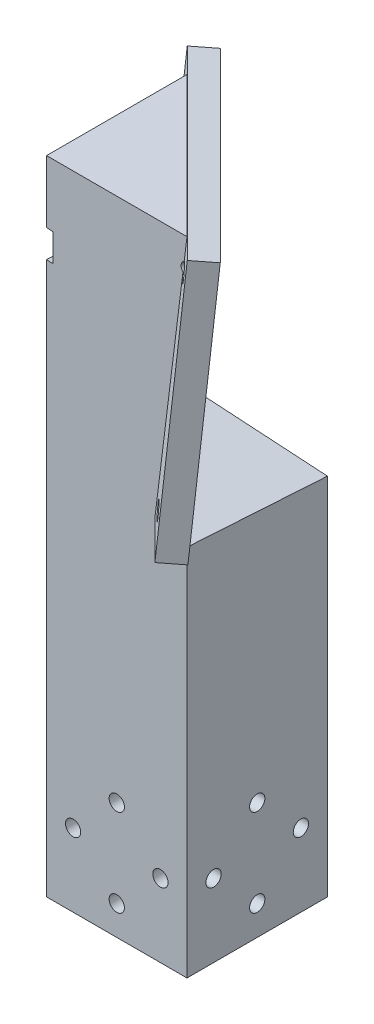
SolidWorks part; units mm, degrees
ref_plane "Front Plane" through (0, 0, 0) normal (0, 0, 1) x (1, 0, 0)
ref_plane "Top Plane" through (0, 0, 0) normal (0, 1, 0) x (1, 0, 0)
ref_plane "Right Plane" through (0, 0, 0) normal (1, 0, 0) x (0, 0, -1)
sketch "Sketch1" plane through (0, 0, 0) normal (0, 1, 0) x (1, 0, 0)
  line L1 (-15.2813, -15.2813) -> (15.2813, -15.2813)
  line L2 (-15.2813, -15.2813) -> (-15.2813, 15.2813)
  line L3 (-15.2813, 15.2813) -> (15.2813, 15.2813)
  line L4 (15.2813, -15.2813) -> (15.2813, 15.2813)
  line L5 (-15.2813, -15.2813) -> (15.2813, 15.2813) construction
  line L6 (-15.2813, 15.2813) -> (15.2813, -15.2813) construction
  point P0 (0, 0)
  point P5 (0, 0)
  dimension "D1" = 30.5626
extrude "Boss-Extrude1" add sketch "Sketch1" along normal blind 139.7 contours L1 L4 L3 L2
ref_plane "Plane2" through (0, 0, 0) normal (0.7071, 0, 0.7071) x (0.7071, 0, -0.7071)
sketch "Sketch2" plane through (0, 0, 0) normal (0.7071, 0, 0.7071) x (0.7071, 0, -0.7071)
  line L4 (5.1193, 139.7) -> (0, 81.186)
  line L5 (0, 81.186) -> (21.611, 79.2953)
  line L8 (5.1193, 139.7) -> (21.611, 139.7)
  line L9 (21.611, 139.7) -> (21.611, 79.2953)
  line L10 (21.611, 0) -> (21.611, 139.7) construction
  line L11 (0, 139.7) -> (21.611, 139.7) construction
  line L12 (0, 0) -> (0, 139.7) construction
  point P1 (0, 0)
  point P2 (18.9957, 142.978)
  point P3 (0, 0)
  point P11 (-4.8066, 82.7675)
  point P12 (0, 0)
  point P14 (0, 0)
  dimension "D2" = 58.7375
  dimension "D1" = 5
extrude "Cut-Extrude1" cut sketch "Sketch2" against normal through all and the other way through all
sketch "Sketch4" plane through (-4.9843, 0.6167, 4.9843) normal (0.7044, -0.0872, -0.7044) x (-0.6991, 0.0865, -0.7098)
  line L0 (-16.3448, 141.5684) -> (40.5893, 136.6062)
  line L1 (40.5893, 136.6062) -> (35.6272, 79.6721)
  line L2 (35.6272, 79.6721) -> (-21.307, 84.6342)
  line L3 (-21.307, 84.6342) -> (-16.3448, 141.5684)
  line L4 (28.5517, 137.6554) -> (-4.3072, 140.5192) construction
  line L5 (2.0641, 23.6823) -> (-2.0641, -23.6823) construction
  point P6 (12.1223, 139.0873)
  dimension "D1" = 57.15
extrude "Boss-Extrude2" add sketch "Sketch4" against normal up to vertex (5.0998 mm away) up to point (15.2813, 139.7, 15.2813)
sketch "Sketch5" plane through (-4.9843, 0.6167, 4.9843) normal (0.7044, -0.0872, -0.7044) x (-0.6991, 0.0865, -0.7098)
  line L0 (19.7125, 122.5204) -> (9.7502, 123.3887)
  line L1 (9.7502, 123.3887) -> (9.2293, 117.4113)
  line L2 (9.2293, 117.4113) -> (19.1915, 116.5431)
  line L3 (19.1915, 116.5431) -> (19.7125, 122.5204)
  line L6 (-10.8662, 134.4614) -> (33.9638, 130.5542) construction
  line L7 (33.9638, 130.5542) -> (30.0566, 85.7241) construction
  line L8 (30.0566, 85.7241) -> (-14.7734, 89.6313) construction
  line L9 (-14.7734, 89.6313) -> (-10.8662, 134.4614) construction
  line L10 (40.5893, 136.6062) -> (-16.3448, 141.5684) construction
  line L11 (-16.3448, 141.5684) -> (-21.307, 84.6342) construction
  line L12 (2.0641, 23.6823) -> (-2.0641, -23.6823) construction
  line L13 (35.6272, 79.6721) -> (40.5893, 136.6062) construction
  line L15 (-5.6318, 96.6232) -> (22.2624, 94.192) construction
  line L16 (-5.6318, 96.6232) -> (-3.2007, 124.5174) construction
  line L17 (-3.2007, 124.5174) -> (24.6936, 122.0863) construction
  line L18 (22.2624, 94.192) -> (24.6936, 122.0863) construction
  line L19 (-5.6318, 96.6232) -> (24.6936, 122.0863) construction
  line L20 (-3.2007, 124.5174) -> (22.2624, 94.192) construction
  circle A0 centre (33.9638, 130.5542) radius 1.8
  circle A1 centre (-10.8662, 134.4614) radius 1.8
  circle A2 centre (-14.7734, 89.6313) radius 1.8
  circle A3 centre (30.0566, 85.7241) radius 1.8
  point P10 (11.5488, 132.5078)
  point P13 (38.1083, 108.1392)
  point P14 (32.0102, 108.1392)
  point P15 (9.5309, 109.3547)
  point P20 (10.7465, 123.3019)
  point P21 (23.478, 108.1392)
  dimension "D6" = 3.6
  dimension "D1" = 45
  dimension "D2" = 28
  dimension "D3" = 10
  dimension "D4" = 6
  dimension "D5" = 5
extrude "Cut-Extrude2" cut sketch "Sketch5" against normal through all
sketch "Sketch6" plane through (0, 0, 0) normal (1, 0, 0) x (0, 0, -1)
  line L0 (0, 25.4) -> (0, 6.4) construction
  line L1 (-9.5, 15.9) -> (9.5, 15.9) construction
  line L2 (-15.2813, 0) -> (15.2813, 0) construction
  circle A0 centre (0, 25.4) radius 1.6625
  circle A1 centre (-9.5, 15.9) radius 1.6625
  circle A2 centre (9.5, 15.9) radius 1.6625
  circle A3 centre (0, 6.4) radius 1.6625
  point P5 (0, 15.9)
  point P6 (0, 15.9)
  dimension "D3" = 3.325
  dimension "D1" = 19
  dimension "D2" = 25.4
extrude "Cut-Extrude3" cut sketch "Sketch6" against normal through all and the other way through all
mirror "Mirror1" about plane through (0, 0, 0) normal (0.7071, 0, 0.7071) of "Cut-Extrude3"
equation "\"tolerance\"= .2mm"
equation "\"id square tube\"= 1.375in - ( .078in * 2 )"
equation "\"angle down\"= 5deg"
equation "\"D1@Sketch1\"=\"id square tube\"-(2*\"tolerance\")"
equation "\"D1@Sketch2\"=\"angle down\""
equation "\"D3@Sketch6\"=\"tolerance\"+3.125mm"
equation "\"height\"= 5.5in"
equation "\"D1@Boss-Extrude1\"=\"height\""
